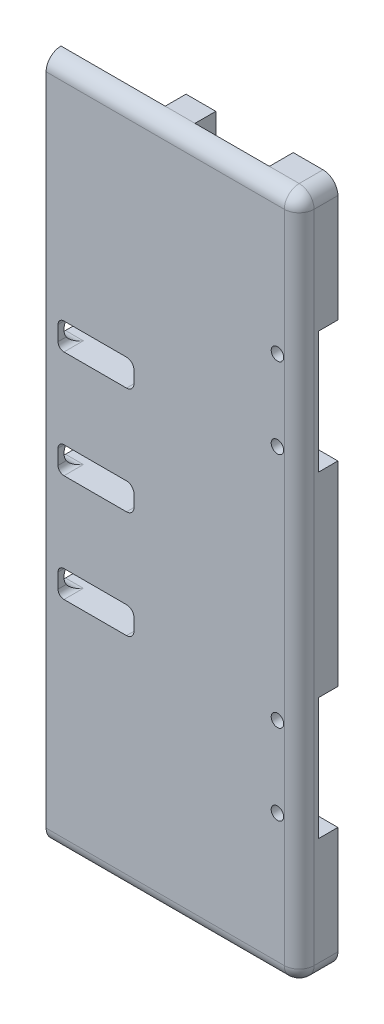
SolidWorks part; units mm, degrees
ref_plane "Front Plane" through (0, 0, 0) normal (0, 0, 1) x (1, 0, 0)
ref_plane "Top Plane" through (0, 0, 0) normal (0, 1, 0) x (1, 0, 0)
ref_plane "Right Plane" through (0, 0, 0) normal (1, 0, 0) x (0, 0, -1)
sketch "Sketch1" plane through (0, 0, 0) normal (0, 0, 1) x (1, 0, 0)
  line L0 (0, 115) -> (85, 115) construction
  line L1 (0, 0) -> (85, 0)
  line L2 (0, 0) -> (0, 230)
  line L3 (0, 230) -> (85, 230)
  line L4 (85, 0) -> (85, 230)
  line L6 (85, 187) -> (72.5, 187) construction
  line L7 (85, 187) -> (85, 148.5) construction
  line L8 (85, 148.5) -> (72.5, 148.5) construction
  line L9 (72.5, 187) -> (72.5, 148.5) construction
  circle A0 centre (77.7, 181.8) radius 2.1
  circle A1 centre (77.7, 154.8) radius 2.1
  circle A2 centre (77.7, 75.2) radius 2.1
  circle A3 centre (77.7, 48.2) radius 2.1
  dimension "D7" = 4.2
  dimension "D9" = 4.2
  dimension "D1" = 85
  dimension "D2" = 230
  dimension "D3" = 38.5
  dimension "D4" = 12.5
  dimension "D5" = 43
  dimension "D6" = 7.3
  dimension "D8" = 5.2
  dimension "D10" = 27
extrude "Boss-Extrude2" add sketch "Sketch1" along normal blind 13 contours A1
sketch "Sketch2" plane through (0, 0, 0) normal (0, 0, -1) x (-1, 0, 0)
  line L0 (-85, 115) -> (0, 115) construction
  line L1 (-85, 0) -> (-85, 230) construction
  line L2 (0, 230) -> (0, 0) construction
  line L4 (-29.5308, 140.7802) -> (0, 140.7802)
  line L5 (-29.5308, 140.7802) -> (-29.5308, 90.8014)
  line L6 (-29.5308, 90.8014) -> (0, 90.8014)
  line L7 (0, 140.7802) -> (0, 90.8014)
fillet "Fillet1" radius 5 2 edges at (85, 0, 6.5) (85, 230, 6.5)
fillet "Fillet2" radius 5 5 edges at (40, 0, 13) (83.5355, 1.4645, 13) (85, 115, 13) (83.5355, 228.5355, 13) (40, 230, 13)
sketch "Sketch4" plane through (0, 0, 13) normal (0, 0, 1) x (1, 0, 0)
  line L0 (0, 115) -> (80, 115) construction
  line L1 (0, 225) -> (0, 5) construction
  line L2 (80, 5) -> (80, 225) construction
  line L4 (7, 119.5) -> (27, 119.5)
  line L5 (4.5, 117) -> (4.5, 113) construction
  line L6 (7, 110.5) -> (27, 110.5) construction
  line L7 (29.5, 117) -> (29.5, 113)
  line L9 (7, 110.5) -> (6, 110.5) construction
  line L10 (6, 110.5) -> (27, 110.5)
  line L13 (7, 119.5) -> (6, 119.5)
  line L14 (7, 119.5) -> (7, 110.5)
  line L15 (7, 110.5) -> (6, 110.5)
  line L16 (4, 117.5) -> (4, 112.5)
  line L21 (0, 133) -> (80, 133) construction
  line L26 (7, 155.5) -> (6, 155.5)
  line L27 (4, 148.5) -> (4, 153.5)
  line L28 (7, 146.5) -> (6, 146.5)
  line L29 (7, 146.5) -> (27, 146.5)
  line L30 (29.5, 149) -> (29.5, 153)
  line L31 (7, 155.5) -> (27, 155.5)
  line L32 (6, 155.5) -> (27, 155.5)
  line L33 (7, 74.5) -> (27, 74.5)
  line L34 (7, 74.5) -> (6, 74.5)
  line L35 (4, 81.5) -> (4, 76.5)
  line L36 (7, 83.5) -> (6, 83.5)
  line L37 (7, 83.5) -> (27, 83.5)
  line L38 (29.5, 81) -> (29.5, 77)
  arc A0 (7, 110.5) -> (4.5, 113) centre (7, 113) cw construction
  arc A1 (29.5, 113) -> (27, 110.5) centre (27, 113) cw
  arc A2 (27, 119.5) -> (29.5, 117) centre (27, 117) cw
  arc A3 (7, 119.5) -> (4.5, 117) centre (7, 117) ccw construction
  arc A7 (6, 110.5) -> (4, 112.5) centre (6, 112.5) cw
  arc A8 (4, 117.5) -> (6, 119.5) centre (6, 117.5) cw
  arc A9 (6, 155.5) -> (4, 153.5) centre (6, 153.5) ccw
  arc A10 (4, 148.5) -> (6, 146.5) centre (6, 148.5) ccw
  arc A11 (27, 146.5) -> (29.5, 149) centre (27, 149) ccw
  arc A12 (29.5, 153) -> (27, 155.5) centre (27, 153) ccw
  arc A13 (6, 74.5) -> (4, 76.5) centre (6, 76.5) cw
  arc A14 (4, 81.5) -> (6, 83.5) centre (6, 81.5) cw
  arc A15 (27, 83.5) -> (29.5, 81) centre (27, 81) cw
  arc A16 (29.5, 77) -> (27, 74.5) centre (27, 77) cw
  point P12 (4.5, 110.5)
  point P15 (29.5, 110.5)
  point P20 (4.5, 119.5)
  point P21 (6.8868, 110.5)
  point P22 (0, 0)
  point P24 (6.4368, 110.5)
  point P27 (8.8336, 110.5)
  point P28 (6.0684, 110.5)
  point P32 (4, 115)
  dimension "D4" = 2.5
  dimension "D9" = 2
  dimension "D1" = 25
  dimension "D2" = 9
  dimension "D3" = 4.5
  dimension "D8" = 4
  dimension "D12" = 18
sketch "Sketch5" plane through (0, 0, 0) normal (-1, 0, 0) x (0, 0, 1)
  line L0 (0, 115) -> (13, 115) construction
  line L1 (0, 230) -> (0, 0) construction
  line L2 (13, 117) -> (13, 113) construction
  line L3 (13, 225) -> (13, 5) construction
  line L4 (0, 119.5) -> (6.5, 119.5)
  line L5 (0, 119.5) -> (0, 110.5)
  line L6 (0, 110.5) -> (6.5, 110.5)
  line L7 (11, 115) -> (11, 110.5) construction
  line L8 (0, 133) -> (13, 133) construction
  line L9 (0, 146.5) -> (6.5, 146.5)
  line L10 (0, 155.5) -> (6.5, 155.5)
  line L11 (0, 146.5) -> (0, 155.5)
  line L12 (0, 83.5) -> (0, 74.5)
  line L13 (0, 74.5) -> (6.5, 74.5)
  line L14 (0, 83.5) -> (6.5, 83.5)
  arc A0 (6.5, 110.5) -> (6.5, 119.5) centre (6.5, 115) ccw
  arc A1 (6.5, 155.5) -> (6.5, 146.5) centre (6.5, 151) cw
  arc A2 (6.5, 74.5) -> (6.5, 83.5) centre (6.5, 79) ccw
  point P14 (11, 110.5)
  line M11 (0, 230) -> (0, 0)
  dimension "D3" = 9
  dimension "D1" = 9
  dimension "D2" = 2
  dimension "D4" = 18
extrude "Cut-Extrude2" cut sketch "Sketch5" against normal blind 35 contours L6 A0 L4 M11 | L9 A1 L10 L11 | L12 L13 A2 L14
extrude "Cut-Extrude3" cut sketch "Sketch4" against normal blind 14
sketch "Sketch6" plane through (0, 0, 0) normal (0, 0, -1) x (-1, 0, 0)
  line L0 (0, 115) -> (-35, 115) construction
  line L1 (0, 110.5) -> (0, 119.5) construction
  line L2 (-35, 110.5) -> (-35, 119.5) construction
  line L3 (0, 110.5) -> (0, 83.5) construction
  line L4 (0, 110.9) -> (-33, 110.9)
  line L5 (0, 110.9) -> (0, 119.1)
  line L6 (0, 119.1) -> (-33, 119.1)
  line L7 (-33, 110.9) -> (-33, 119.1)
  line L8 (0, 107.9) -> (-6.5, 107.9) construction
  line L9 (0, 110.9) -> (-6.5, 110.9)
  line L10 (0, 110.9) -> (0, 104.9) construction
  line L11 (0, 104.9) -> (-6.5, 104.9) construction
  line L12 (-6.5, 110.9) -> (-6.5, 104.9) construction
  line L13 (0, 133) -> (-85, 133) construction
  line L14 (0, 146.5) -> (0, 119.5) construction
  line L15 (-85, 5) -> (-85, 225) construction
  circle A0 centre (-4, 107.9) radius 1.55
  circle A1 centre (-12, 107.9) radius 1.55
  circle A2 centre (-4, 122.1) radius 1.55
  circle A3 centre (-12, 122.1) radius 1.55
  circle A4 centre (-12, 158.1) radius 1.55
  circle A5 centre (-4, 158.1) radius 1.55
  circle A6 centre (-4, 143.9) radius 1.55
  circle A7 centre (-12, 143.9) radius 1.55
  circle A8 centre (-4, 86.1) radius 1.55
  circle A9 centre (-4, 71.9) radius 1.55
  circle A10 centre (-12, 86.1) radius 1.55
  circle A11 centre (-12, 71.9) radius 1.55
  dimension "D5" = 3.1
  dimension "D1" = 8.2
  dimension "D2" = 33
  dimension "D3" = 6.5
  dimension "D4" = 6
  dimension "D6" = 4
  dimension "D7" = 8
  dimension "D8" = 18
extrude "Cut-Extrude4" cut sketch "Sketch6" against normal blind 7 contours A1 | A0 | A3 | A2 | A4 | A7 | A6 | A5 | A10 | A8 | A9 | A11
sketch "Sketch9" plane through (0, 0, 0) normal (0, 0, -1) x (-1, 0, 0)
  line L0 (-85, 5) -> (-85, 225) construction
  line L1 (0, 230) -> (-70, 230)
  line L2 (0, 230) -> (0, 170)
  line L3 (0, 170) -> (-70, 170)
  line L4 (-70, 230) -> (-70, 170)
  line L5 (0, 0) -> (-70, 0)
  line L6 (0, 0) -> (0, 60)
  line L7 (0, 60) -> (-70, 60)
  line L8 (-70, 0) -> (-70, 60)
  line L10 (-70, 170) -> (-45, 170)
  line L11 (-70, 170) -> (-70, 60)
  line L12 (-70, 60) -> (-45, 60)
  line L13 (-45, 170) -> (-45, 60)
  line M15 (0, 119.5) -> (0, 146.5)
  line M16 (0, 230) -> (-80, 230)
  line M20 (-80, 0) -> (0, 0)
  line M21 (0, 0) -> (0, 74.5)
  dimension "D1" = 15
  dimension "D2" = 60
  dimension "D3" = 60
  dimension "D4" = 25
extrude "Cut-Extrude5" cut sketch "Sketch9" against normal blind 8 contours L4 L3 M16 M15 | L13 L3 L11 L7 | L8 L7 M20 M21
sketch "Sketch13" plane through (0, 0, 8) normal (0, 0, -1) x (-1, 0, 0)
  line L0 (0, 230) -> (-70, 230) construction
  line L1 (0, 0) -> (-80, 0) construction
  line L2 (0, 0) -> (0, 230) construction
  line L3 (0, 230) -> (-80, 230) construction
  line L4 (-80, 0) -> (-80, 230) construction
  line L5 (-40, 230) -> (-40, 0) construction
  line L7 (-45, 230) -> (-35, 230)
  line L8 (-45, 230) -> (-45, 0)
  line L9 (-45, 0) -> (-35, 0)
  line L10 (-35, 230) -> (-35, 0)
  circle A0 centre (-10, 15) radius 5
  dimension "D2" = 10
  dimension "D1" = 80
  dimension "D3" = 10
  dimension "D4" = 15
  dimension "D5" = 40
  dimension "D6" = 10
extrude "Boss-Extrude4" add sketch "Sketch13" along normal blind 7
sketch "Sketch14" plane through (0, 0, 0) normal (0, 0, -1) x (-1, 0, 0)
  line L0 (-77.7, 181.8) -> (-77.7, 154.8) construction
  line L1 (-77.7, 168.3) -> (-85, 168.3) construction
  line L2 (-85, 5) -> (-85, 225) construction
  line L3 (-77.7, 75.2) -> (-77.7, 48.2) construction
  line L4 (-77.7, 61.7) -> (-85, 61.7) construction
  line L5 (-70, 230) -> (-70, 0) construction
  line L6 (-85, 188.8) -> (-70, 188.8)
  line L7 (-85, 188.8) -> (-85, 147.8)
  line L8 (-85, 147.8) -> (-70, 147.8)
  line L9 (-70, 188.8) -> (-70, 147.8)
  line L10 (-70, 230) -> (-70, 0) construction
  line L11 (-85, 82.2) -> (-70, 82.2)
  line L12 (-85, 82.2) -> (-85, 41.2)
  line L13 (-85, 41.2) -> (-70, 41.2)
  line L14 (-70, 82.2) -> (-70, 41.2)
  dimension "D1" = 41
  dimension "D2" = 41
extrude "Cut-Extrude6" cut sketch "Sketch14" against normal blind 6.5
sketch "Sketch16" plane through (35, 0, 0) normal (-1, 0, 0) x (0, 0, 1)
  circle A0 centre (6.5, 115) radius 4.5
  arc A1 (6.5, 110.5) -> (6.5, 119.5) centre (6.5, 115) ccw construction
  circle A2 centre (6.5, 151) radius 4.5
  circle A3 centre (6.5, 79) radius 4.5
  arc A4 (6.5, 74.5) -> (6.5, 83.5) centre (6.5, 79) ccw construction
  arc A5 (6.5, 146.5) -> (6.5, 155.5) centre (6.5, 151) ccw construction
extrude "Cut-Extrude8" cut sketch "Sketch16" against normal blind 25
sketch "Sketch20" plane through (0, 0, 1) normal (0, 0, -1) x (-1, 0, 0)
  line L0 (-35, 0) -> (-35, 60) construction
  line L1 (-35, 12) -> (-45, 12)
  line L2 (-35, 12) -> (-35, 39)
  line L3 (-35, 39) -> (-45, 39)
  line L4 (-45, 12) -> (-45, 39)
  line L5 (-45, 110.7574) -> (-45, 83.2426) construction
  line L6 (-45, 0) -> (-35, 0) construction
  dimension "D1" = 12
  dimension "D2" = 27
extrude "Cut-Extrude9" cut sketch "Sketch20" against normal up to surface (7 mm away)
